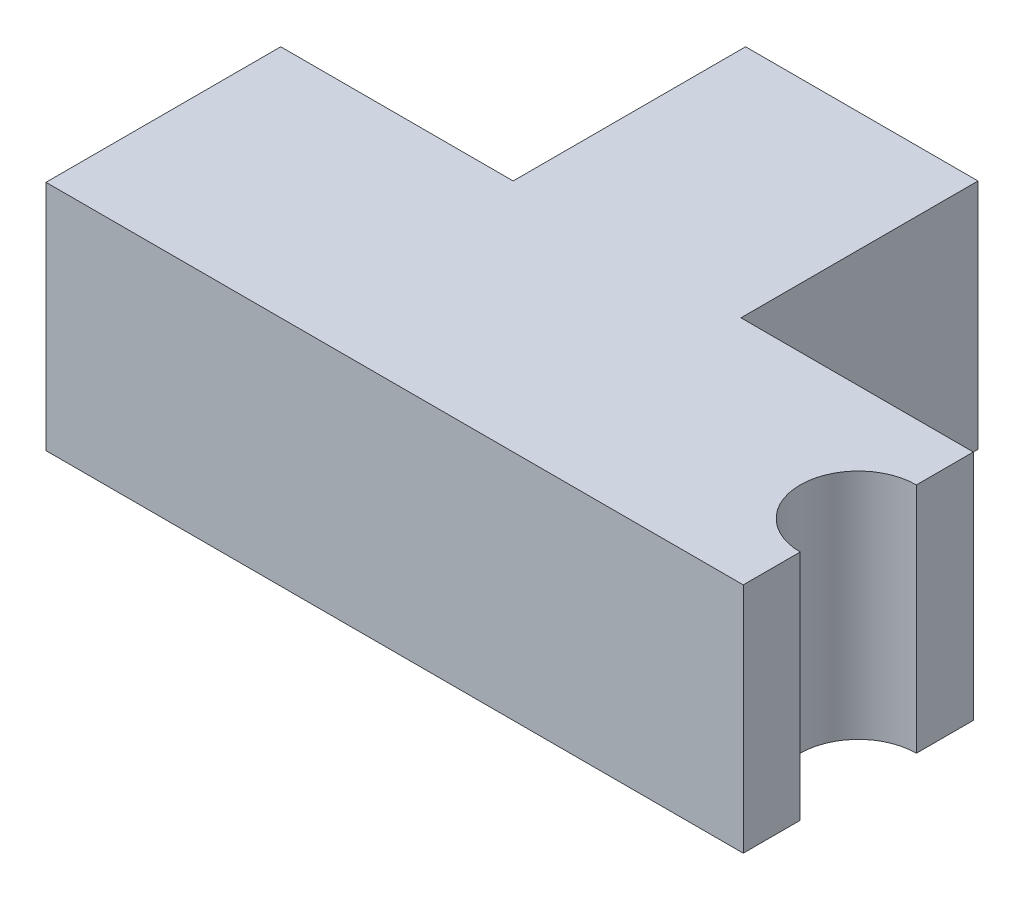
SolidWorks part; units mm, degrees
ref_plane "Front Plane" through (0, 0, 0) normal (0, 0, 1) x (1, 0, 0)
ref_plane "Top Plane" through (0, 0, 0) normal (0, 1, 0) x (1, 0, 0)
ref_plane "Right Plane" through (0, 0, 0) normal (1, 0, 0) x (0, 0, -1)
sketch "Sketch1" plane through (0, 0, 0) normal (0, 1, 0) x (1, 0, 0)
  line L0 (4.85, 4.9005) -> (14.85, 4.9005)
  line L1 (-15.15, -4.9995) -> (14.85, -4.9995)
  line L2 (-15.15, -4.9995) -> (-15.15, 5.1005)
  line L3 (-15.15, 5.1005) -> (-5.15, 5.1005)
  line L4 (14.85, -4.9995) -> (14.85, 4.9005)
  line L5 (-15.15, -4.9995) -> (14.85, 4.9005) construction
  line L6 (-15.15, 5.1005) -> (14.85, -4.9995) construction
  line L7 (-5.15, 15.1005) -> (4.85, 15.1005)
  line L8 (-5.15, 15.1005) -> (-5.15, 5.1005)
  line L10 (4.85, 15.1005) -> (4.85, 4.9005)
  point P0 (0, 0)
  dimension "D1" = 30
  dimension "D2" = 9.9
  dimension "D3" = 10
  dimension "D4" = 10
  dimension "D5" = 10
  dimension "D6" = 10.1
extrude "Boss-Extrude1" add sketch "Sketch1" along normal blind 10
sketch "Sketch2" plane through (0, 10, 0) normal (0, 1, 0) x (1, 0, 0)
  line L0 (14.85, -4.9995) -> (14.85, 4.9005) construction
  circle A0 centre (14.85, -0.0495) radius 2.5
  dimension "D1" = 5
extrude "Cut-Extrude1" cut sketch "Sketch2" against normal through all
